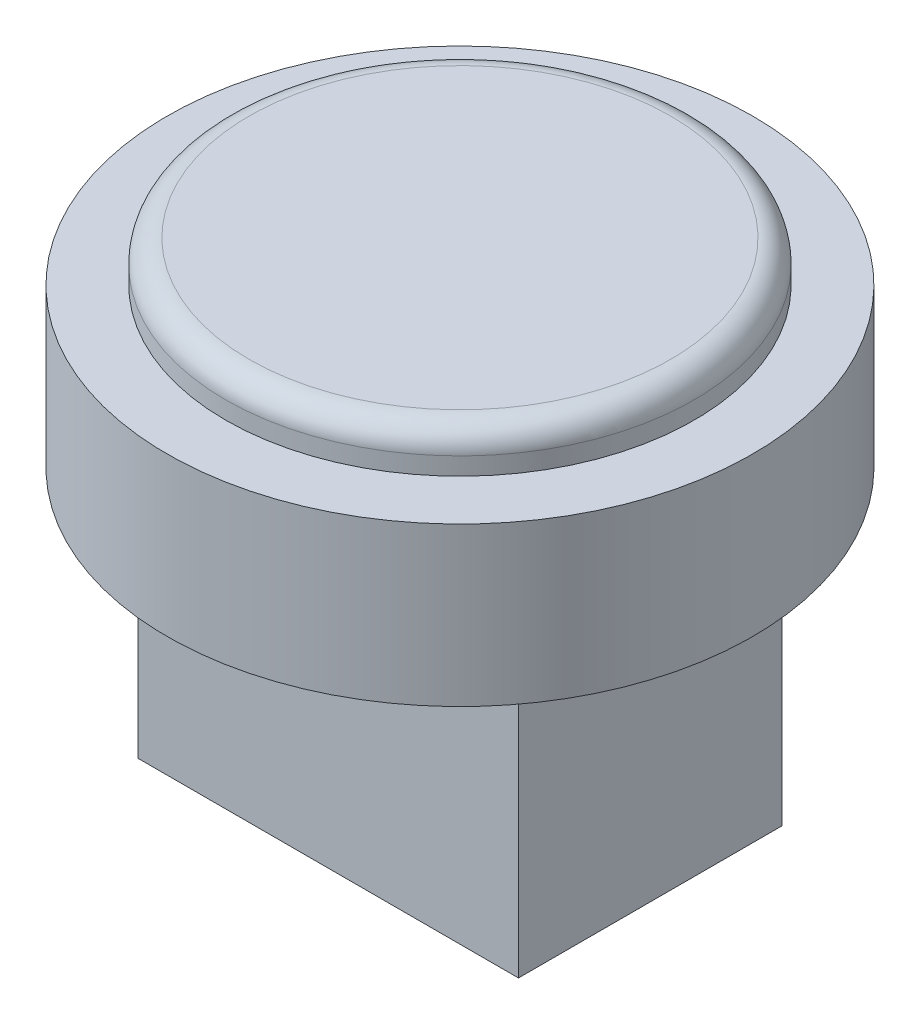
SolidWorks part; units mm, degrees
material "ABS Black"
ref_plane "Front Plane" through (0, 0, 0) normal (0, 0, 1) x (1, 0, 0)
ref_plane "Top Plane" through (0, 0, 0) normal (0, 1, 0) x (1, 0, 0)
ref_plane "Right Plane" through (0, 0, 0) normal (1, 0, 0) x (0, 0, -1)
sketch "Sketch1" plane through (0, 0, 0) normal (0, 1, 0) x (1, 0, 0)
  circle A0 centre (0, 0) radius 5
  dimension "D1" = 10
extrude "Boss-Extrude1" add sketch "Sketch1" along normal blind 2.7
sketch "Sketch2" plane through (0, 2.7, 0) normal (0, 1, 0) x (1, 0, 0)
  circle A0 centre (0, 0) radius 4
  dimension "D1" = 8
extrude "Boss-Extrude2" add sketch "Sketch2" along normal blind 0.7
fillet "Fillet1" radius 0.4 1 edges at (0, 3.4, 4)
sketch "Sketch3" plane through (0, 0, 0) normal (0, -1, 0) x (1, 0, 0)
  line L1 (-3.25, 2.25) -> (3.25, 2.25)
  line L2 (-3.25, 2.25) -> (-3.25, -2.25)
  line L3 (-3.25, -2.25) -> (3.25, -2.25)
  line L4 (3.25, 2.25) -> (3.25, -2.25)
  point P4 (-3.25, 0)
  point P6 (0, 2.25)
  dimension "D1" = 6.5
  dimension "D2" = 4.5
extrude "Boss-Extrude3" add sketch "Sketch3" along normal blind 4.8
